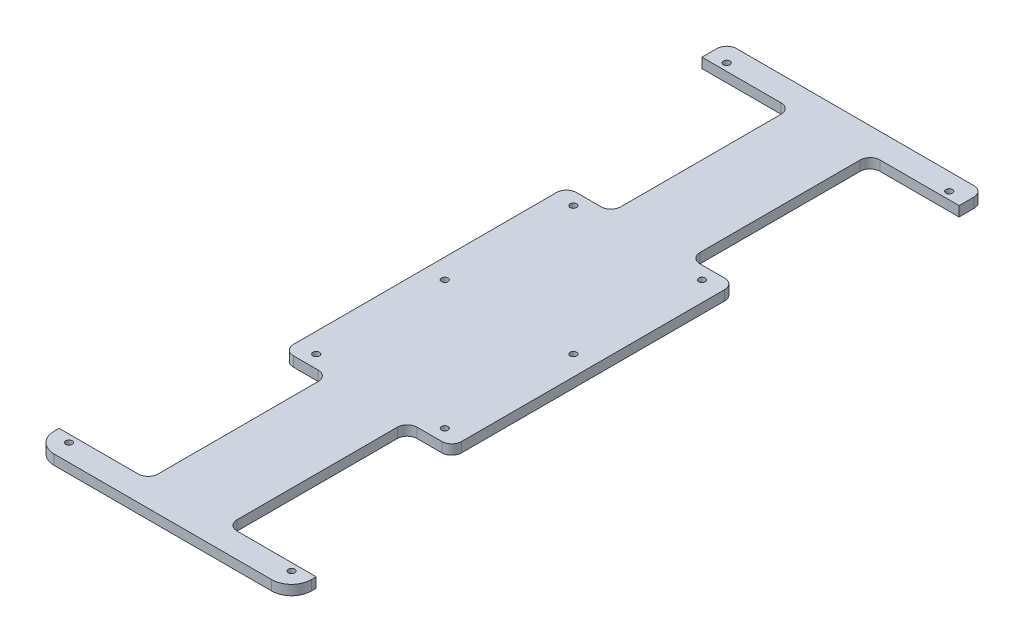
SolidWorks part; units mm, degrees
ref_plane "Front Plane" through (0, 0, 0) normal (0, 0, 1) x (1, 0, 0)
ref_plane "Top Plane" through (0, 0, 0) normal (0, 1, 0) x (1, 0, 0)
ref_plane "Right Plane" through (0, 0, 0) normal (1, 0, 0) x (0, 0, -1)
sketch "Sketch1" plane through (0, 0, 0) normal (0, 1, 0) x (1, 0, 0)
  line L0 (0, 0) -> (130, 0)
  line L1 (0, 0) -> (130, 0) construction
  line L2 (0, 0) -> (0, 350) construction
  line L3 (0, 350) -> (130, 350) construction
  line L4 (130, 0) -> (130, 350) construction
  line L5 (130, 0) -> (130, 12.5)
  line L6 (130, 12.5) -> (85, 12.5)
  line L7 (85, 12.5) -> (85, 103.5)
  line L11 (85, 246.5) -> (85, 337.5)
  line L12 (85, 337.5) -> (130, 337.5)
  line L13 (130, 337.5) -> (130, 350)
  line L14 (130, 350) -> (0, 350)
  line L15 (0, 350) -> (0, 337.5)
  line L16 (0, 337.5) -> (45, 337.5)
  line L17 (45, 337.5) -> (45, 246.5)
  line L21 (45, 103.5) -> (45, 12.5)
  line L22 (45, 12.5) -> (0, 12.5)
  line L23 (0, 12.5) -> (0, 0)
  line L24 (45, 246.5) -> (22.5, 246.5)
  line L25 (22.5, 246.5) -> (22.5, 103.5)
  line L26 (22.5, 103.5) -> (45, 103.5)
  line L27 (85, 246.5) -> (107.5, 246.5)
  line L28 (107.5, 246.5) -> (107.5, 103.5)
  line L29 (107.5, 103.5) -> (85, 103.5)
  dimension "D1" = 130
  dimension "D2" = 350
  dimension "D3" = 45
  dimension "D4" = 91
  dimension "D5" = 22.5
  dimension "D6" = 143
extrude "Boss-Extrude1" add sketch "Sketch1" along normal blind 5
fillet "Fillet1" radius 10 2 edges at (130, 2.5, 0) (0, 2.5, 0)
fillet "Fillet2" radius 5 6 edges at (0, 2.5, -350) (130, 2.5, -350) (107.5, 2.5, -246.5) (107.5, 2.5, -103.5) (22.5, 2.5, -103.5) (22.5, 2.5, -246.5)
sketch "Sketch2" plane through (0, 5, 0) normal (0, 1, 0) x (1, 0, 0)
  line L2 (32.5, 240) -> (32.5, 110) construction
  line L3 (22.5, 175) -> (32.5, 175) construction
  line L4 (22.5, 241.5) -> (22.5, 108.5) construction
  line L5 (65, 350) -> (65, 0) construction
  line L6 (125, 350) -> (5, 350) construction
  line L7 (10, 0) -> (120, 0) construction
  circle A0 centre (32.5, 240) radius 1.65
  circle A1 centre (32.5, 175) radius 1.65
  circle A2 centre (32.5, 110) radius 1.65
  circle A3 centre (97.5, 110) radius 1.65
  circle A4 centre (97.5, 175) radius 1.65
  circle A5 centre (97.5, 240) radius 1.65
  dimension "D3" = 3.3
  dimension "D1" = 10
  dimension "D2" = 130
extrude "Cut-Extrude1" cut sketch "Sketch2" against normal through all
sketch "Sketch3" plane through (0, 5, 0) normal (0, 1, 0) x (1, 0, 0)
  line L0 (0, 12.5) -> (8.75, 12.5) construction
  line L1 (45, 12.5) -> (0, 12.5) construction
  line L2 (8.75, 12.5) -> (8.75, 8.75) construction
  line L3 (65, 0) -> (65, 57.6288) construction
  line L4 (10, 0) -> (120, 0) construction
  circle A0 centre (8.75, 8.75) radius 1.65
  circle A1 centre (121.25, 8.75) radius 1.65
  dimension "D3" = 3.3
  dimension "D1" = 8.75
  dimension "D2" = 3.75
extrude "Cut-Extrude2" cut sketch "Sketch3" against normal through all
sketch "Sketch4" plane through (0, 5, 0) normal (0, 1, 0) x (1, 0, 0)
  line L0 (0, 337.5) -> (8.75, 337.5) construction
  line L1 (0, 337.5) -> (45, 337.5) construction
  line L2 (8.75, 337.5) -> (8.75, 341.25) construction
  line L3 (65, 350) -> (65, 288.2737) construction
  line L4 (125, 350) -> (5, 350) construction
  circle A0 centre (8.75, 341.25) radius 1.65
  circle A1 centre (121.25, 341.25) radius 1.65
  dimension "D3" = 3.3
  dimension "D1" = 8.75
  dimension "D2" = 3.75
extrude "Cut-Extrude3" cut sketch "Sketch4" against normal through all
fillet "Fillet3" radius 5 8 edges at (85, 2.5, -246.5) (45, 2.5, -246.5) (85, 2.5, -103.5) (45, 2.5, -103.5) (45, 2.5, -12.5) (85, 2.5, -12.5) (45, 2.5, -337.5) (85, 2.5, -337.5)
